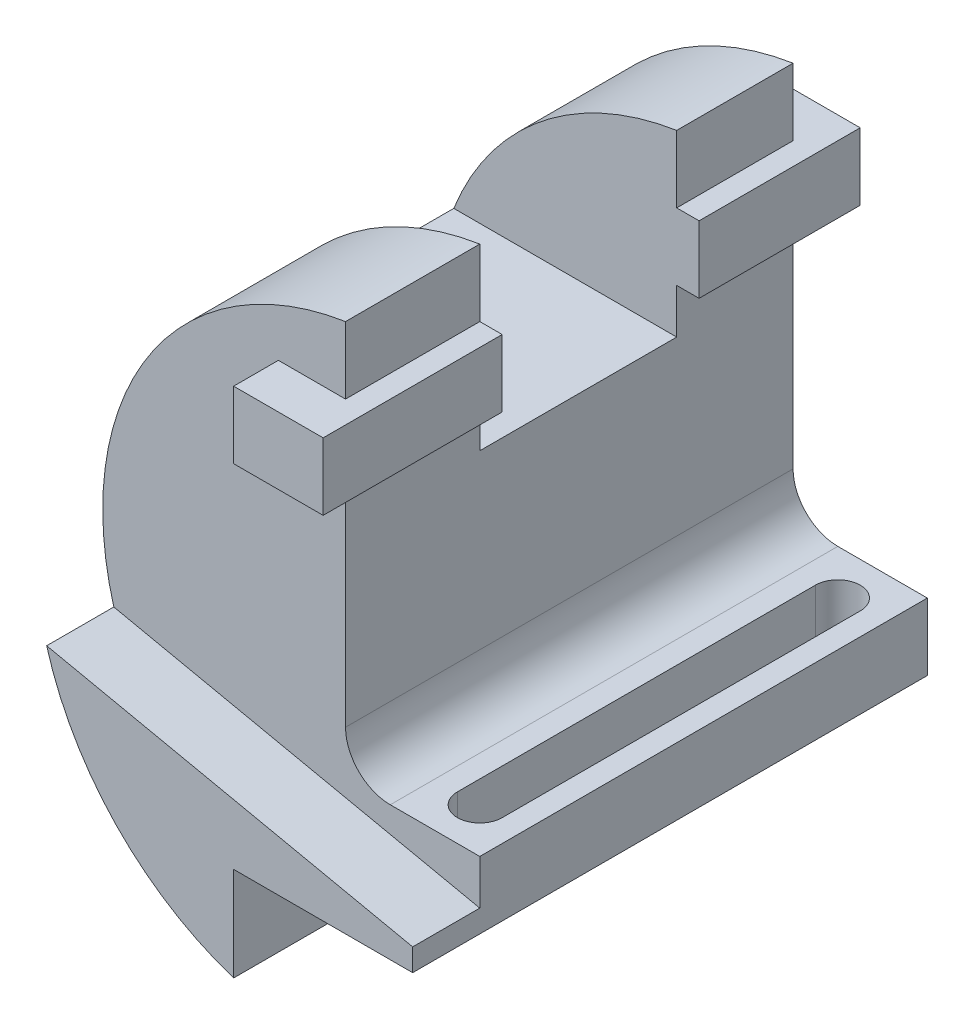
SolidWorks part; units mm, degrees
material "Alliage 1060"
ref_plane "Plan de face" through (0, 0, 0) normal (0, 0, 1) x (1, 0, 0)
ref_plane "Plan de dessus" through (0, 0, 0) normal (0, 1, 0) x (1, 0, 0)
ref_plane "Plan de droite" through (0, 0, 0) normal (1, 0, 0) x (0, 0, -1)
sketch "Esquisse1" plane through (0, 0, 0) normal (0, 0, 1) x (1, 0, 0)
  line L0 (-10, 63.467) -> (-10, -15.033)
  line L1 (0, -25.033) -> (20, -25.033)
  line L2 (20, -25.033) -> (20, -40.033)
  line L3 (20, -40.033) -> (-20, -40.033)
  line L4 (-20, -40.033) -> (-20, -61.0579)
  line L5 (0, 61.6077) -> (0, -61.6077) construction
  line L6 (-90.3006, 0) -> (90.3006, 0) construction
  arc A0 (-10, 63.467) -> (-20, -61.0579) centre (0, 0) ccw
  arc A1 (-10, -15.033) -> (0, -25.033) centre (0, -15.033) ccw
  point P14 (-10, -25.033)
  dimension "D5" = 64.25
  dimension "D7" = 10
  dimension "D1" = 10
  dimension "D2" = 20
  dimension "D3" = 40
  dimension "D4" = 15
  dimension "D6" = 88.5
extrude "Boss.-Extru.1" add sketch "Esquisse1" along normal blind 115
sketch "Esquisse2" plane through (0, 0, 115) normal (0, 0, 1) x (1, 0, 0)
  line L0 (20, -35.033) -> (-61.778, -17.6505)
  line L1 (20, -40.033) -> (20, -25.033) construction
  line L7 (-20, -61.0579) -> (-20, -40.033)
  line L8 (-20, -40.033) -> (20, -40.033)
  line L9 (20, -40.033) -> (20, -25.033)
  line L10 (20, -25.033) -> (0, -25.033)
  line L11 (-10, -15.033) -> (-10, 63.467)
  line L14 (20, -35.033) -> (20, -25.033)
  line L15 (20, -25.033) -> (0, -25.033)
  line L16 (-10, -15.033) -> (-10, 63.467)
  arc A0 (-10, 63.467) -> (-20, -61.0579) centre (0, 0) ccw construction
  arc A3 (-10, 63.467) -> (-20, -61.0579) centre (0, 0) ccw
  arc A4 (-10, -15.033) -> (0, -25.033) centre (0, -15.033) ccw
  arc A5 (-10, 63.467) -> (-61.778, -17.6505) centre (0, 0) ccw
  arc A6 (-10, -15.033) -> (0, -25.033) centre (0, -15.033) ccw
  dimension "D1" = 5
  dimension "D2" = 78
  dimension "D3" = 0
extrude "Enlèv. mat.-Extru.1" cut sketch "Esquisse2" against normal blind 15
sketch "Esquisse3" plane through (0, 0, 100) normal (0, 0, 1) x (1, 0, 0)
  line L0 (-10, -15.033) -> (-10, 63.467) construction
  line L1 (-25, 48.467) -> (-5, 48.467)
  line L2 (-25, 48.467) -> (-25, 33.467)
  line L3 (-25, 33.467) -> (-5, 33.467)
  line L4 (-5, 48.467) -> (-5, 33.467)
  dimension "D1" = 5
  dimension "D2" = 15
  dimension "D3" = 15
  dimension "D4" = 15
extrude "Boss.-Extru.2" add sketch "Esquisse3" against normal offset from surface (120 mm away) 10 from offset 10
sketch "Esquisse4" plane through (-5, 0, 0) normal (1, 0, 0) x (0, 0, -1)
  line L0 (-100, 63.467) -> (0, 63.467) construction
  line L1 (-70, 63.467) -> (-26, 63.467)
  line L2 (-70, 63.467) -> (-70, 23.467)
  line L3 (-70, 23.467) -> (-26, 23.467)
  line L4 (-26, 63.467) -> (-26, 23.467)
  line L5 (-100, 48.467) -> (-100, 63.467) construction
  dimension "D3" = 40
  dimension "D1" = 30
  dimension "D2" = 44
extrude "Enlèv. mat.-Extru.2" cut sketch "Esquisse4" against normal through all
sketch "Esquisse5" plane through (0, -25.033, 0) normal (0, 1, 0) x (1, 0, 0)
  line L0 (10, 0) -> (10, -100) construction
  line L1 (20, 0) -> (0, 0) construction
  line L2 (20, -100) -> (0, -100) construction
  line L3 (10, -10) -> (10, -90) construction
  line L4 (15, -10) -> (15, -90)
  line L5 (5, -10) -> (5, -90)
  line L6 (-61.778, -100) -> (20, -100) construction
  arc A0 (15, -10) -> (5, -10) centre (10, -10) ccw
  arc A1 (5, -90) -> (15, -90) centre (10, -90) ccw
  point P8 (10, -50)
  dimension "D1" = 5
  dimension "D2" = 80
  dimension "D3" = 10
extrude "Enlèv. mat.-Extru.3" cut sketch "Esquisse5" against normal through all
equation "\"A\" = 64.25"
equation "\"B\" = 88.5"
equation "\"C\"= 44"
equation "\"D5@Esquisse1\"=\"A\""
equation "\"D6@Esquisse1\"=\"B\""
equation "\"D2@Esquisse4\"=\"C\""
